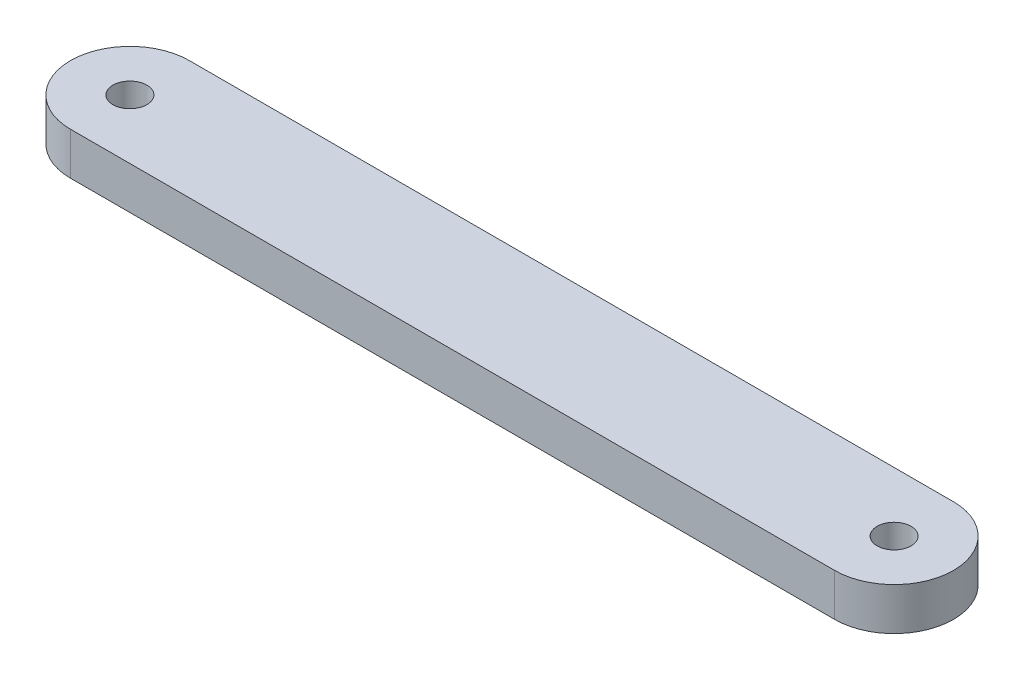
SolidWorks part; units mm, degrees
material "Hexcel AS4C (3000 Filaments)"
ref_plane "Ön Düzlem" through (0, 0, 0) normal (0, 0, 1) x (1, 0, 0)
ref_plane "Üst Düzlem" through (0, 0, 0) normal (0, 1, 0) x (1, 0, 0)
ref_plane "Sağ Düzlem" through (0, 0, 0) normal (1, 0, 0) x (0, 0, -1)
sketch "Çizim1" plane through (0, 0, 0) normal (0, 1, 0) x (1, 0, 0)
  line L0 (-45, 0) -> (45, 0) construction
  line L1 (-45, 7) -> (45, 7)
  line L2 (-45, -7) -> (45, -7)
  arc A0 (-45, 7) -> (-45, -7) centre (-45, 0) ccw
  arc A1 (45, -7) -> (45, 7) centre (45, 0) ccw
  circle A2 centre (-45, 0) radius 2
  circle A3 centre (45, 0) radius 2
  point P2 (0, 0)
  dimension "D1" = 7
  dimension "D3" = 4
  dimension "D2" = 90
extrude "Yükseklik-Ekstrüzyon1" add sketch "Çizim1" along normal mid plane 5
sketch "Çizim2" plane through (0, -2.5, 0) normal (0, -1, 0) x (1, 0, 0)
  circle A0 centre (0, 0) radius 2
  dimension "D1" = 4
extrude "Kes-Ekstrüzyon1" cut sketch "Çizim2" against normal up to surface (2.5 mm away)
